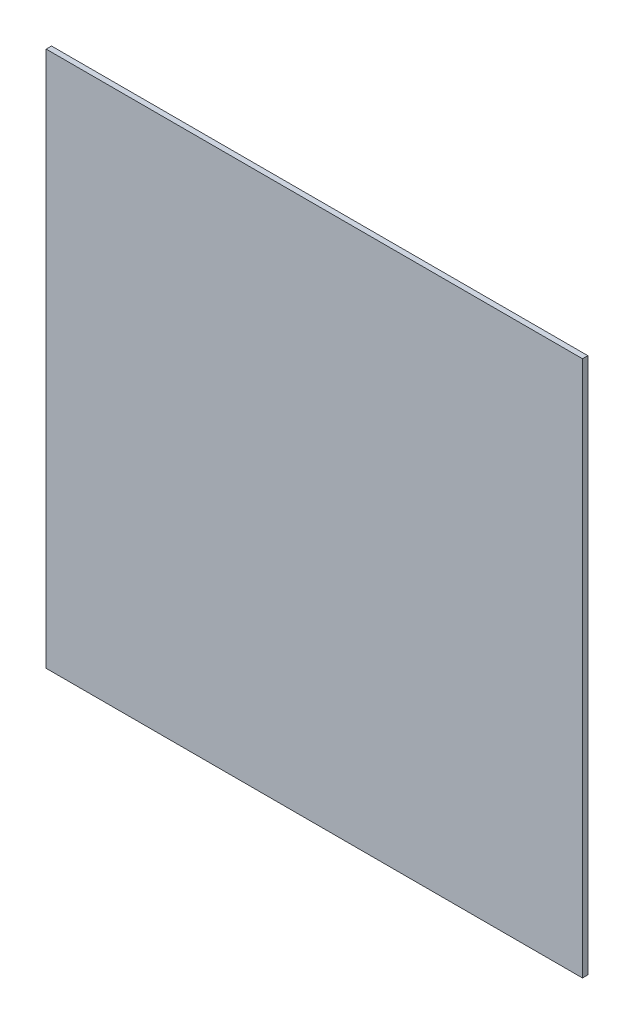
SolidWorks part; units mm, degrees
material "Rubber"
ref_plane "Front Plane" through (0, 0, 0) normal (0, 0, 1) x (1, 0, 0)
ref_plane "Top Plane" through (0, 0, 0) normal (0, 1, 0) x (1, 0, 0)
ref_plane "Right Plane" through (0, 0, 0) normal (1, 0, 0) x (0, 0, -1)
sketch "Sketch1" plane through (0, 0, 0) normal (0, 0, -1) x (1, 0, 0)
  line L1 (0, -10000) -> (10000, -10000)
  line L2 (0, -10000) -> (0, 0)
  line L3 (0, 0) -> (10000, 0)
  line L4 (10000, -10000) -> (10000, 0)
  dimension "D1" = 10000
  dimension "D2" = 10000
extrude "Boss-Extrude1" add sketch "Sketch1" along normal blind 100
